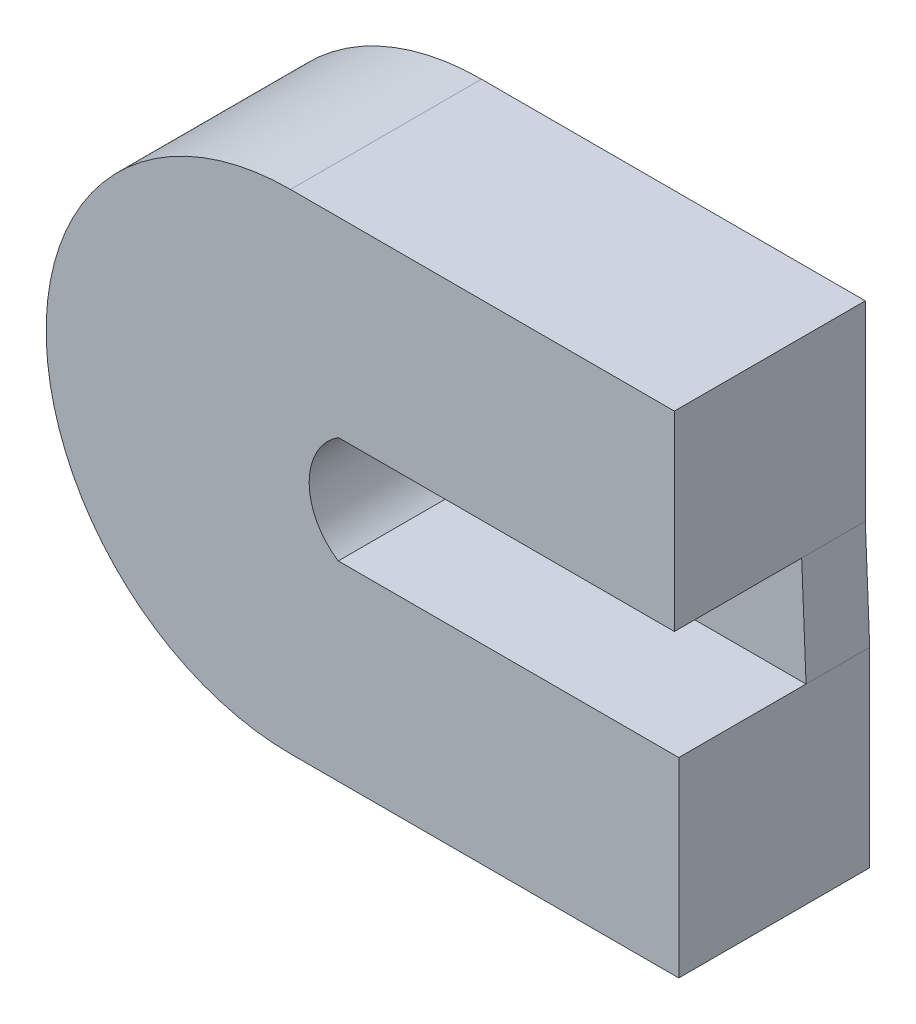
SolidWorks part; units mm, degrees
ref_plane "Front Plane" through (0, 0, 0) normal (0, 0, 1) x (1, 0, 0)
ref_plane "Top Plane" through (0, 0, 0) normal (0, 1, 0) x (1, 0, 0)
ref_plane "Right Plane" through (0, 0, 0) normal (1, 0, 0) x (0, 0, -1)
sketch "Sketch1" plane through (0, 0, 0) normal (0, 0, 1) x (1, 0, 0)
  line L0 (-2, 6.7054) -> (2, 6.7054)
  line L1 (-2, 3.3454) -> (2, 3.3454)
  line L2 (0, -10.3488) -> (0, 11.4341) construction
  line L3 (-3.5, 12.7054) -> (3.5, 12.7054)
  line L4 (3.5, -2.6546) -> (-3.5, -2.6546)
  line L5 (2, 6.7054) -> (8.5625, 6.7054)
  line L6 (8.5625, 6.7054) -> (8.5625, 12.7054)
  line L7 (8.5625, 12.7054) -> (3.5, 12.7054)
  line L8 (3.5, -2.6546) -> (8.7004, -2.6546)
  line L9 (8.7004, -2.6546) -> (8.7004, 3.3454)
  line L10 (8.7004, 3.3454) -> (2, 3.3454)
  arc A1 (-2, 6.7054) -> (-2, 3.3454) centre (-0.9148, 5.0254) ccw
  arc A3 (-3.5, -2.6546) -> (-3.5, 12.7054) centre (-3.5, 5.0254) cw
  point P2 (0, 6.7054)
  point P11 (0, 3.3454)
  point P14 (0, 12.7054)
  point P19 (0, -2.6546)
  dimension "D3" = 1.5
  dimension "D1" = 4
  dimension "D2" = 3.36
  dimension "D4" = 6
  dimension "D5" = 6
  dimension "D6" = 1.5
extrude "Boss-Extrude1" add sketch "Sketch1" along normal blind 6
sketch "Sketch2" plane through (0, 0, 0) normal (0, 0, 1) x (1, 0, 0)
  line L0 (8.5625, 6.7054) -> (8.7004, 3.3454)
  line L3 (8.5625, 6.7054) -> (2.7, 6.7054)
  line L4 (-2, 6.7054) -> (8.5625, 6.7054) construction
  line L5 (2.7, 6.7054) -> (2.7, 3.3454)
  line L6 (8.7004, 3.3454) -> (-2, 3.3454) construction
  line L7 (2.7, 3.3454) -> (8.7004, 3.3454)
  dimension "previous 4.77" = 4.7
extrude "Boss-Extrude2" add sketch "Sketch2" along normal blind 2
